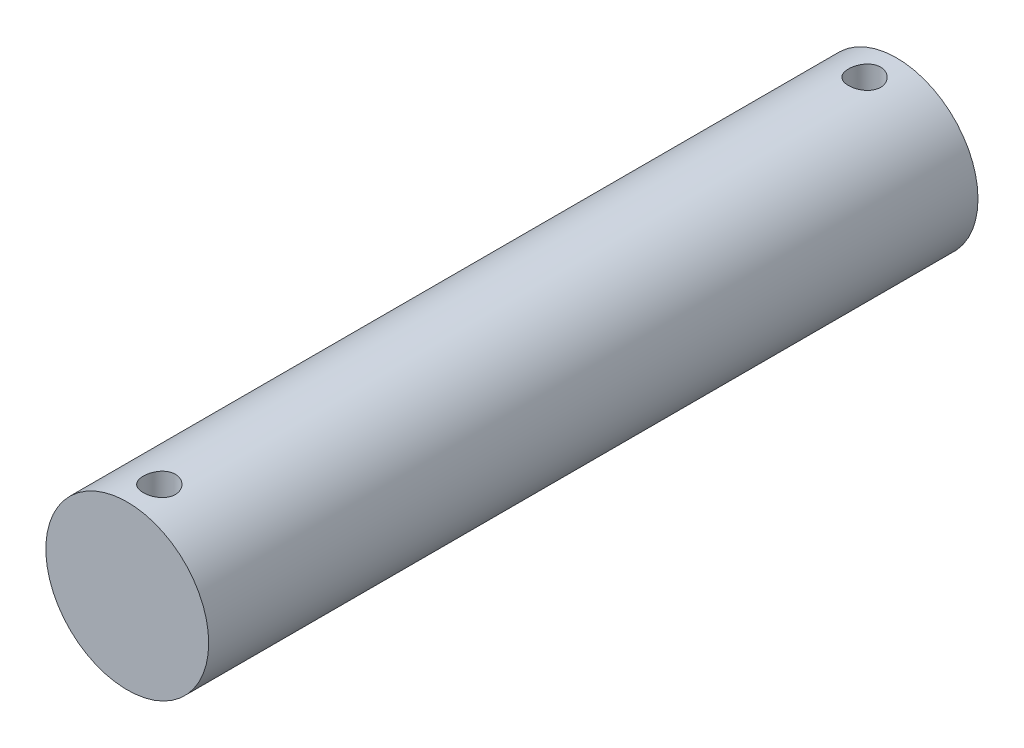
SolidWorks part; units mm, degrees
ref_plane "Front Plane" through (0, 0, 0) normal (0, 0, 1) x (1, 0, 0)
ref_plane "Top Plane" through (0, 0, 0) normal (0, 1, 0) x (1, 0, 0)
ref_plane "Right Plane" through (0, 0, 0) normal (1, 0, 0) x (0, 0, -1)
sketch "Sketch1" plane through (0, 0, 0) normal (0, 0, 1) x (1, 0, 0)
  circle A0 centre (0, 0) radius 6.35
  dimension "D1" = 12.7
extrude "Boss-Extrude1" add sketch "Sketch1" along normal mid plane 60 contours A0
sketch "Sketch2" plane through (0, 0, 0) normal (0, 1, 0) x (1, 0, 0)
  line L0 (6.35, 30) -> (-6.35, 30) construction
  line L1 (-6.35, -30) -> (6.35, -30) construction
  circle A0 centre (0, -27.5) radius 1.25
  circle A1 centre (0, 27.5) radius 1.25
  dimension "D2" = 2.5
  dimension "D4" = 2.5
  dimension "D1" = 2.5
  dimension "D3" = 2.5
extrude "Cut-Extrude1" cut sketch "Sketch2" against normal mid plane 50
